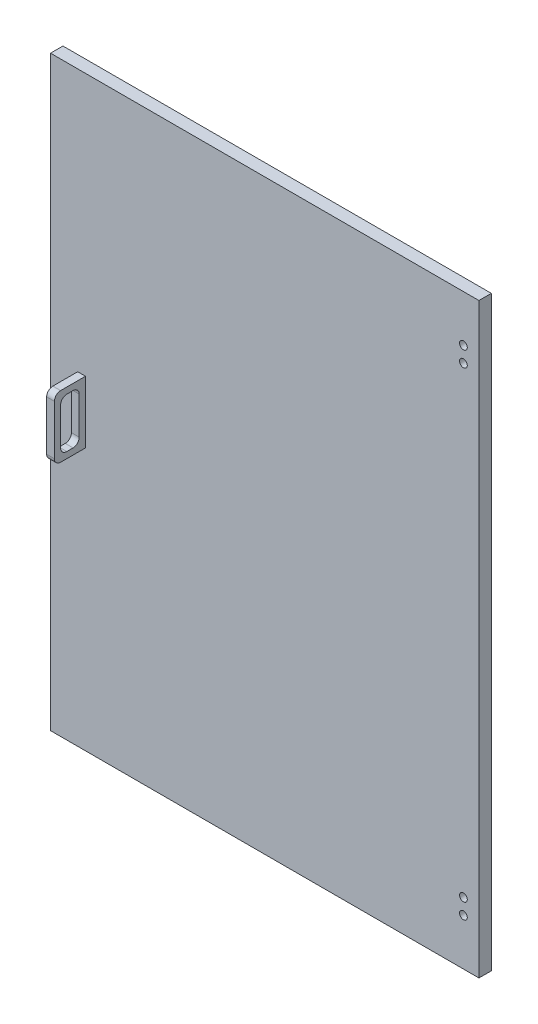
SolidWorks part; units mm, degrees
material "PVC 0.007 Plasticized"
ref_plane "Front Plane" through (0, 0, 0) normal (0, 0, 1) x (1, 0, 0)
ref_plane "Top Plane" through (0, 0, 0) normal (0, 1, 0) x (1, 0, 0)
ref_plane "Right Plane" through (0, 0, 0) normal (1, 0, 0) x (0, 0, -1)
sketch "Sketch1" plane through (0, 0, 0) normal (0, 0, 1) x (1, 0, 0)
  line L0 (-87.63, 120.015) -> (87.63, 120.015)
  line L7 (-87.63, 120.015) -> (-87.63, -120.015)
  line L8 (-87.63, -120.015) -> (87.63, -120.015)
  line L9 (87.63, 120.015) -> (87.63, -120.015)
  point P0 (0, 0)
  dimension "D1" = 240.03
  dimension "D2" = 175.26
  dimension "D3" = 87.63
  dimension "D4" = 120.015
extrude "Boss-Extrude1" add sketch "Sketch1" against normal blind 5.08
sketch "Sketch2" plane through (0, 0, 0) normal (0, 0, 1) x (1, 0, 0)
  line L0 (87.63, -120.015) -> (87.63, 120.015) construction
  line L1 (87.63, 120.015) -> (-87.63, 120.015) construction
  line L2 (55, 0) -> (-55, 0) construction
  circle A0 centre (81.28, 100.965) radius 1.5875
  circle A1 centre (81.28, 94.615) radius 1.5875
  circle A2 centre (81.28, -94.615) radius 1.5875
  circle A3 centre (81.28, -100.965) radius 1.5875
  point P10 (81.28, -94.615)
  dimension "D1" = 3.175
  dimension "D2" = 3.175
  dimension "D3" = 6.35
  dimension "D4" = 19.05
  dimension "D5" = 6.35
extrude "Cut-Extrude1" cut sketch "Sketch2" against normal through all
sketch "Sketch3" plane through (0, 0, 0) normal (0, 0, 1) x (1, 0, 0)
  line L0 (-76.5175, -12.7) -> (-73.3425, -12.7)
  line L1 (-76.5175, -12.7) -> (-76.5175, 12.7)
  line L2 (-76.5175, 12.7) -> (-73.3425, 12.7)
  line L3 (-73.3425, -12.7) -> (-73.3425, 12.7)
  line L4 (-76.5175, -12.7) -> (-73.3425, 12.7) construction
  line L5 (-76.5175, 12.7) -> (-73.3425, -12.7) construction
  line L6 (2.794, 0) -> (-2.794, 0) construction
  line L7 (-87.63, 120.015) -> (-87.63, -120.015) construction
  point P0 (-74.93, 0)
  dimension "D1" = 25.4
  dimension "D2" = 3.175
  dimension "D3" = 12.7
extrude "Boss-Extrude2" add sketch "Sketch3" along normal blind 12.7
sketch "Sketch4" plane through (-73.3425, 0, 0) normal (1, 0, 0) x (0, 0, -1)
  line L0 (9.779, 0) -> (-9.779, 0) construction
  line L1 (-10.16, -10.16) -> (-2.54, -10.16)
  line L2 (-10.16, -10.16) -> (-10.16, 10.16)
  line L3 (-10.16, 10.16) -> (-2.54, 10.16)
  line L4 (-2.54, -10.16) -> (-2.54, 10.16)
  line L5 (-10.16, -10.16) -> (-2.54, 10.16) construction
  line L6 (-10.16, 10.16) -> (-2.54, -10.16) construction
  line L7 (-12.7, 12.7) -> (0, 12.7) construction
  line L8 (-12.7, -12.7) -> (-12.7, 12.7) construction
  line L9 (0, 143.3597) -> (0, -143.3597) construction
  point P0 (-6.35, 0)
  dimension "D1" = 2.54
  dimension "D2" = 2.54
  dimension "D3" = 2.54
extrude "Cut-Extrude2" cut sketch "Sketch4" against normal through all
fillet "Fillet1" radius 2.54 6 edges at (-74.93, 10.16, 10.16) (-74.93, -10.16, 10.16) (-74.93, 10.16, 2.54) (-74.93, -10.16, 2.54) (-74.93, -12.7, 12.7) (-74.93, 12.7, 12.7)
